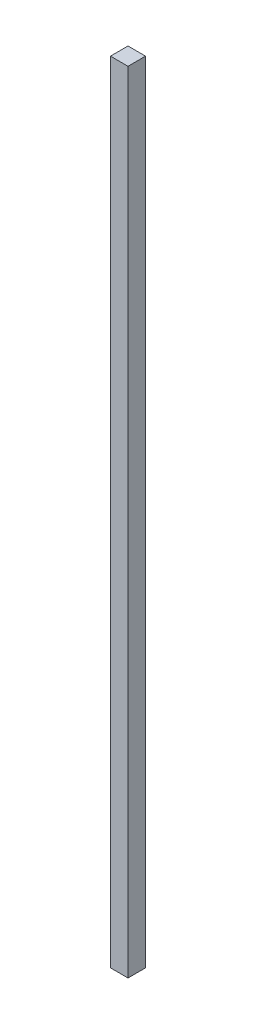
SolidWorks part; units mm, degrees
ref_plane "Front Plane" through (0, 0, 0) normal (0, 0, 1) x (1, 0, 0)
ref_plane "Top Plane" through (0, 0, 0) normal (0, 1, 0) x (1, 0, 0)
ref_plane "Right Plane" through (0, 0, 0) normal (1, 0, 0) x (0, 0, -1)
sketch "Sketch1" plane through (0, 0, 0) normal (0, 1, 0) x (1, 0, 0)
  line L1 (-10, 10) -> (10, 10)
  line L2 (-10, 10) -> (-10, -10)
  line L3 (-10, -10) -> (10, -10)
  line L4 (10, 10) -> (10, -10)
  line L5 (-10, 10) -> (10, -10) construction
  line L6 (-10, -10) -> (10, 10) construction
  point P0 (0, 0)
  dimension "D1" = 20
  dimension "D2" = 20
extrude "Boss-Extrude1" add sketch "Sketch1" along normal blind 900
